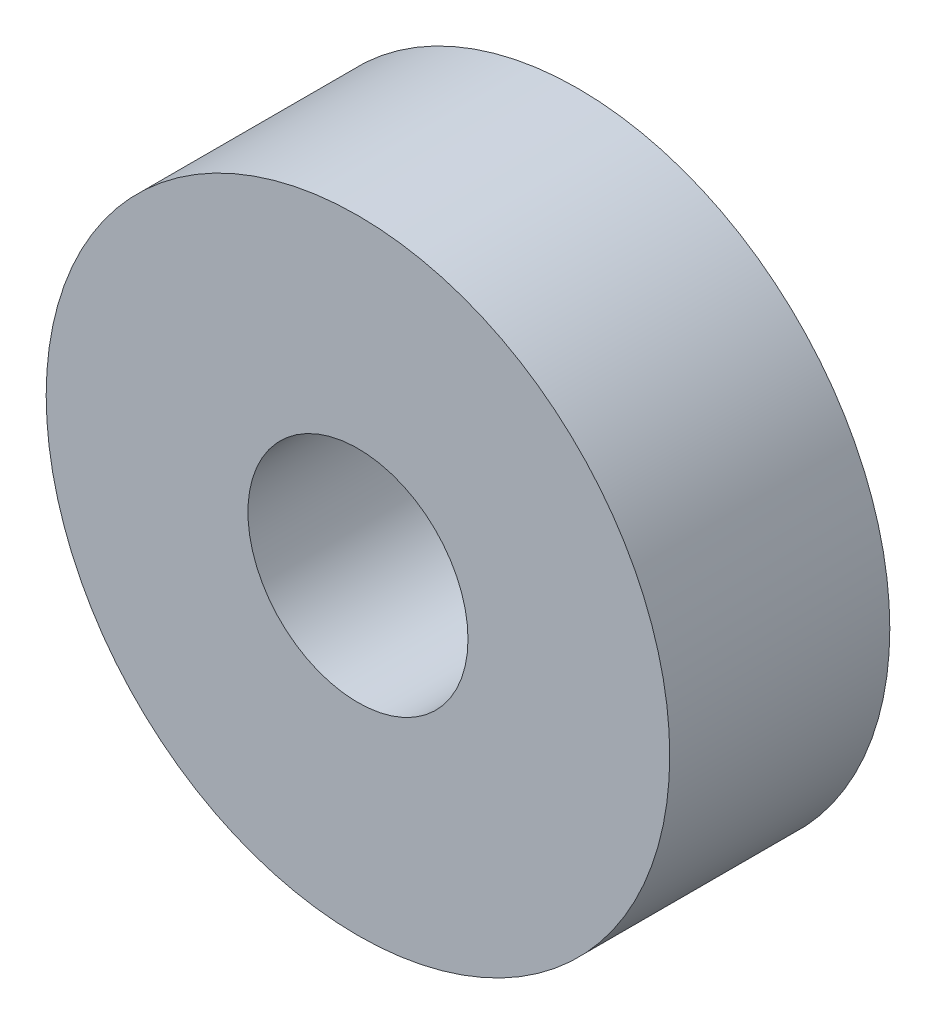
SolidWorks part; units mm, degrees
material "Plain Carbon Steel"
ref_plane "Front Plane" through (0, 0, 0) normal (0, 0, 1) x (1, 0, 0)
ref_plane "Top Plane" through (0, 0, 0) normal (0, 1, 0) x (1, 0, 0)
ref_plane "Right Plane" through (0, 0, 0) normal (1, 0, 0) x (0, 0, -1)
sketch "Sketch1" plane through (0, 0, 0) normal (0, 0, 1) x (1, 0, 0)
  circle A0 centre (0, 0) radius 3
  circle A1 centre (0, 0) radius 8.5
  dimension "D1" = 6
  dimension "D2" = 17
extrude "Boss-Extrude1" add sketch "Sketch1" along normal mid plane 6
